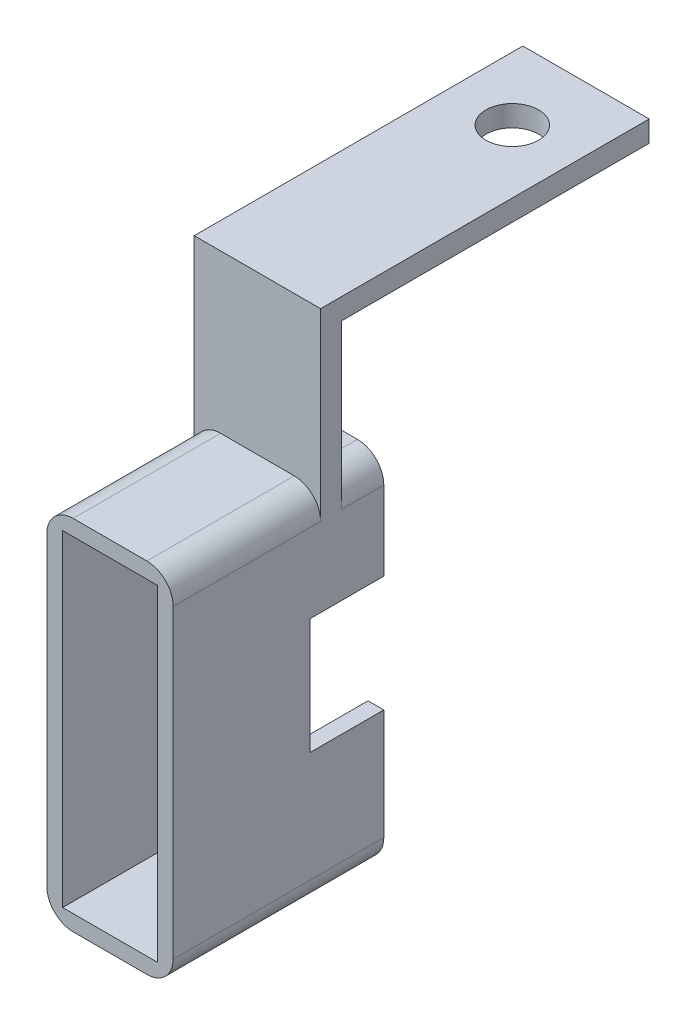
SolidWorks part; units mm, degrees
ref_plane "Plan de face" through (0, 0, 0) normal (0, 0, 1) x (1, 0, 0)
ref_plane "Plan de dessus" through (0, 0, 0) normal (0, 1, 0) x (1, 0, 0)
ref_plane "Plan de droite" through (0, 0, 0) normal (1, 0, 0) x (0, 0, -1)
sketch "Esquisse1" plane through (0, 0, 0) normal (0, 0, 1) x (1, 0, 0)
  line L0 (-20.7757, 15.7218) -> (-20.7757, -15.2782)
  line L1 (-11.7757, 15.7218) -> (-11.7757, -15.2782)
  line L2 (-20.7757, 15.7218) -> (-11.7757, 15.7218)
  line L3 (-20.7757, -15.2782) -> (-11.7757, -15.2782)
  line L4 (-22.2757, 15.7218) -> (-22.2757, -12.7782)
  line L5 (-22.2757, -12.7782) -> (-22.2757, -16.7782)
  line L6 (-22.2757, -16.7782) -> (-10.2757, -16.7782)
  line L7 (-10.2757, -16.7782) -> (-10.2757, 17.2218)
  line L8 (-10.2757, 17.2218) -> (-22.2757, 17.2218)
  line L9 (-22.2757, 17.2218) -> (-22.2757, 15.7218)
  dimension "D1" = 31
  dimension "D2" = 31
  dimension "D3" = 9
  dimension "D4" = 1.5
  dimension "D5" = 34
  dimension "D6" = 1.5
extrude "Boss.-Extru.1" add sketch "Esquisse1" along normal blind 20
sketch "Esquisse3" plane through (0, 17.2218, 0) normal (0, 1, 0) x (1, 0, 0)
  line L0 (-22.2757, -4) -> (-10.2757, -4)
  line L1 (-22.2757, -20) -> (-22.2757, 0) construction
  line L2 (-10.2757, -20) -> (-10.2757, 0) construction
  line L6 (-10.2757, 0) -> (-22.2757, 0) construction
  line L7 (-22.2757, -4) -> (-22.2757, -6)
  line L8 (-22.2757, -6) -> (-10.2757, -6)
  line L9 (-10.2757, -6) -> (-10.2757, -4)
  dimension "D1" = 2
  dimension "D2" = 4
extrude "Boss.-Extru.2" add sketch "Esquisse3" along normal blind 15
sketch "Esquisse4" plane through (0, 0, 4) normal (0, 0, -1) x (-1, 0, 0)
  line L0 (10.2757, 30.2218) -> (22.2757, 30.2218)
  line L1 (10.2757, 32.2218) -> (10.2757, 17.2218) construction
  line L2 (22.2757, 32.2218) -> (22.2757, 17.2218) construction
  line L3 (22.2757, 30.2218) -> (22.2757, 32.2218)
  line L4 (22.2757, 32.2218) -> (10.2757, 32.2218)
  line L5 (10.2757, 32.2218) -> (10.2757, 30.2218)
  dimension "D1" = 2
extrude "Boss.-Extru.3" add sketch "Esquisse4" along normal blind 29.2
sketch "Esquisse5" plane through (0, 32.2218, 0) normal (0, 1, 0) x (1, 0, 0)
  line L0 (-16.2757, -6) -> (-16.2757, 25.2) construction
  line L1 (-22.2757, -6) -> (-10.2757, -6) construction
  line L2 (-22.2757, 25.2) -> (-10.2757, 25.2) construction
  circle A0 centre (-16.2757, 18.2) radius 2.5
  dimension "D1" = 7
extrude "Enlèv. mat.-Extru.3" cut sketch "Esquisse5" against normal blind 10
fillet "Congé1" radius 2.5 2 edges at (-10.2757, -16.7782, 10) (-10.2757, 17.2218, 13)
fillet "Congé2" radius 2.5 4 edges at (-22.2757, 17.2218, 2) (-22.2757, -16.7782, 10) (-22.2757, 17.2218, 13) (-10.2757, 17.2218, 2)
sketch "Esquisse2" plane through (-10.2757, 0, 0) normal (1, 0, 0) x (0, 0, -1)
  line L0 (0, -3.7782) -> (-7, -3.7782)
  line L1 (0, -14.2782) -> (0, 14.7218) construction
  line L2 (-7, -3.7782) -> (-7, 7.2218)
  line L3 (-7, 7.2218) -> (0, 7.2218)
  line L4 (-20, 17.2218) -> (0, 17.2218) construction
  line L5 (-20, -16.7782) -> (0, -16.7782) construction
  line M3 (0, -14.2782) -> (0, 14.7218)
  dimension "D1" = 10
  dimension "D2" = 13
  dimension "D3" = 7
extrude "Enlèv. mat.-Extru.2" cut sketch "Esquisse2" against normal blind 5 and the other way through all contours L3 L2 L0 M3
sketch "Esquisse6" plane through (-22.2757, 0, 0) normal (-1, 0, 0) x (0, 0, 1)
  line L0 (0, 4.2218) -> (7, 4.2218)
  line L1 (0, 14.7218) -> (0, -14.2782) construction
  line L2 (7, 4.2218) -> (7, -4.7782)
  line L3 (7, -4.7782) -> (0, -4.7782)
  line L4 (0, -14.2782) -> (20, -14.2782) construction
  line L5 (4, 14.7218) -> (0, 14.7218) construction
  line M6 (0, 14.7218) -> (0, -14.2782)
  dimension "D1" = 9.5
  dimension "D2" = 10.5
  dimension "D3" = 7
extrude "Enlèv. mat.-Extru.5" cut sketch "Esquisse6" against normal blind 5 and the other way through all contours L3 L2 L0 M6
